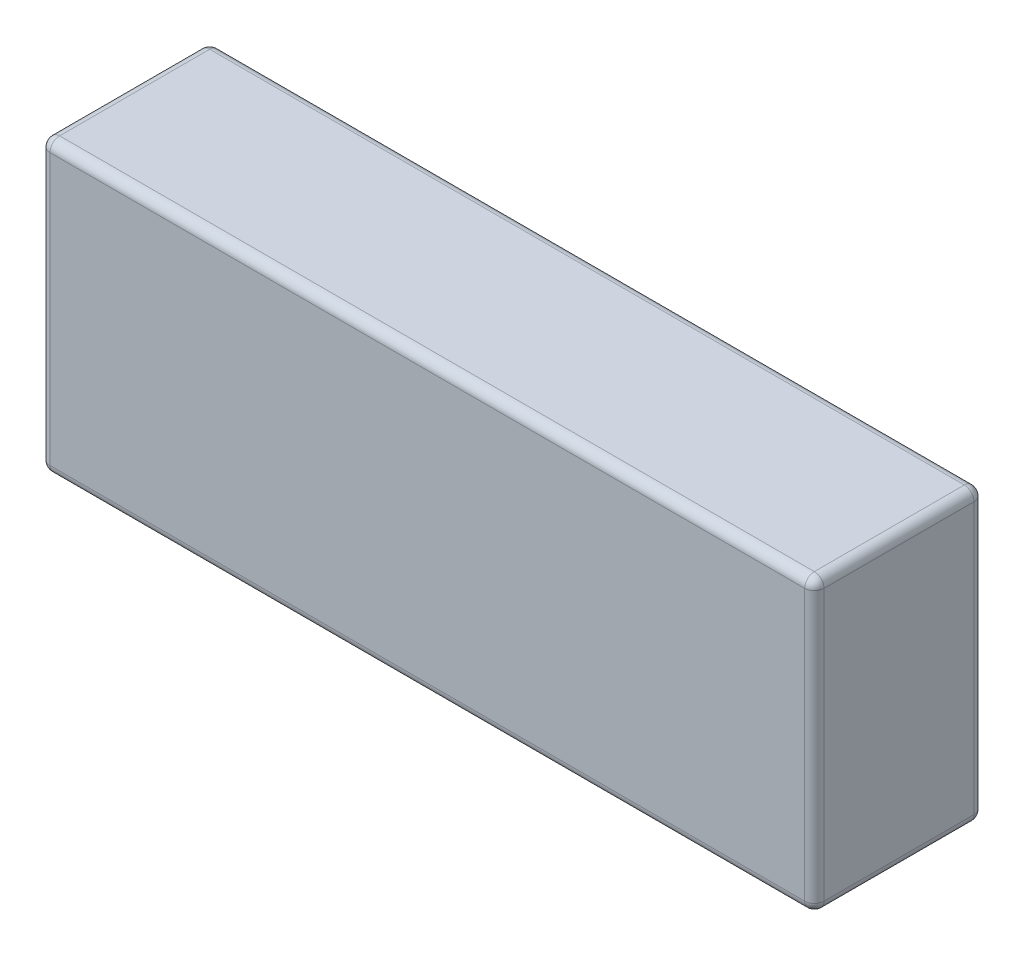
SolidWorks part; units mm, degrees
ref_plane "Plan de face" through (0, 0, 0) normal (0, 0, 1) x (1, 0, 0)
ref_plane "Plan de dessus" through (0, 0, 0) normal (0, 1, 0) x (1, 0, 0)
ref_plane "Plan de droite" through (0, 0, 0) normal (1, 0, 0) x (0, 0, -1)
sketch "Esquisse1" plane through (0, 0, 0) normal (0, 0, 1) x (1, 0, 0)
  line L1 (0, 0) -> (160, 0)
  line L2 (0, 0) -> (0, 60)
  line L3 (0, 60) -> (160, 60)
  line L4 (160, 0) -> (160, 60)
  dimension "D1" = 160
  dimension "D2" = 60
extrude "Boss.-Extru.1" add sketch "Esquisse1" along normal blind 35
fillet "Congé1" radius 2 12 edges at (0, 0, 17.5) (80, 0, 0) (0, 30, 0) (160, 0, 17.5) (160, 30, 0) (160, 60, 17.5) (0, 60, 17.5) (80, 60, 0) (80, 60, 35) (160, 30, 35) (80, 0, 35) (0, 30, 35)
